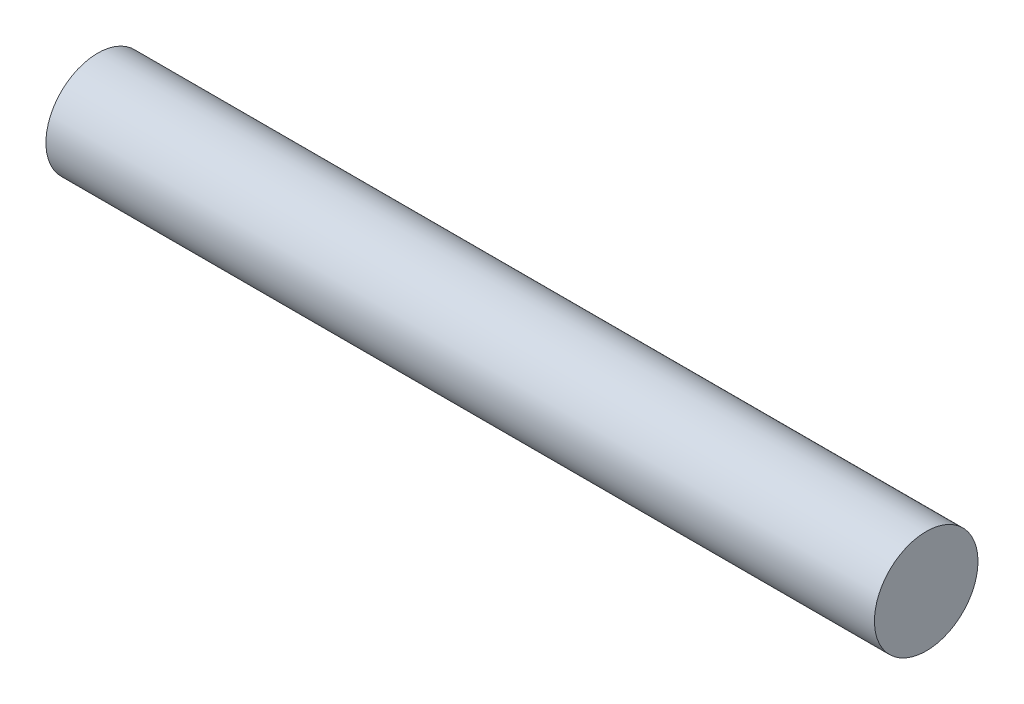
SolidWorks part; units mm, degrees
ref_plane "Front Plane" through (0, 0, 0) normal (0, 0, 1) x (1, 0, 0)
ref_plane "Top Plane" through (0, 0, 0) normal (0, 1, 0) x (1, 0, 0)
ref_plane "Right Plane" through (0, 0, 0) normal (1, 0, 0) x (0, 0, -1)
sketch "Sketch1" plane through (0, 0, 0) normal (1, 0, 0) x (0, 0, -1)
  circle A0 centre (0, 0) radius 1
  dimension "D1" = 2
extrude "Boss-Extrude1" add sketch "Sketch1" along normal mid plane 16
